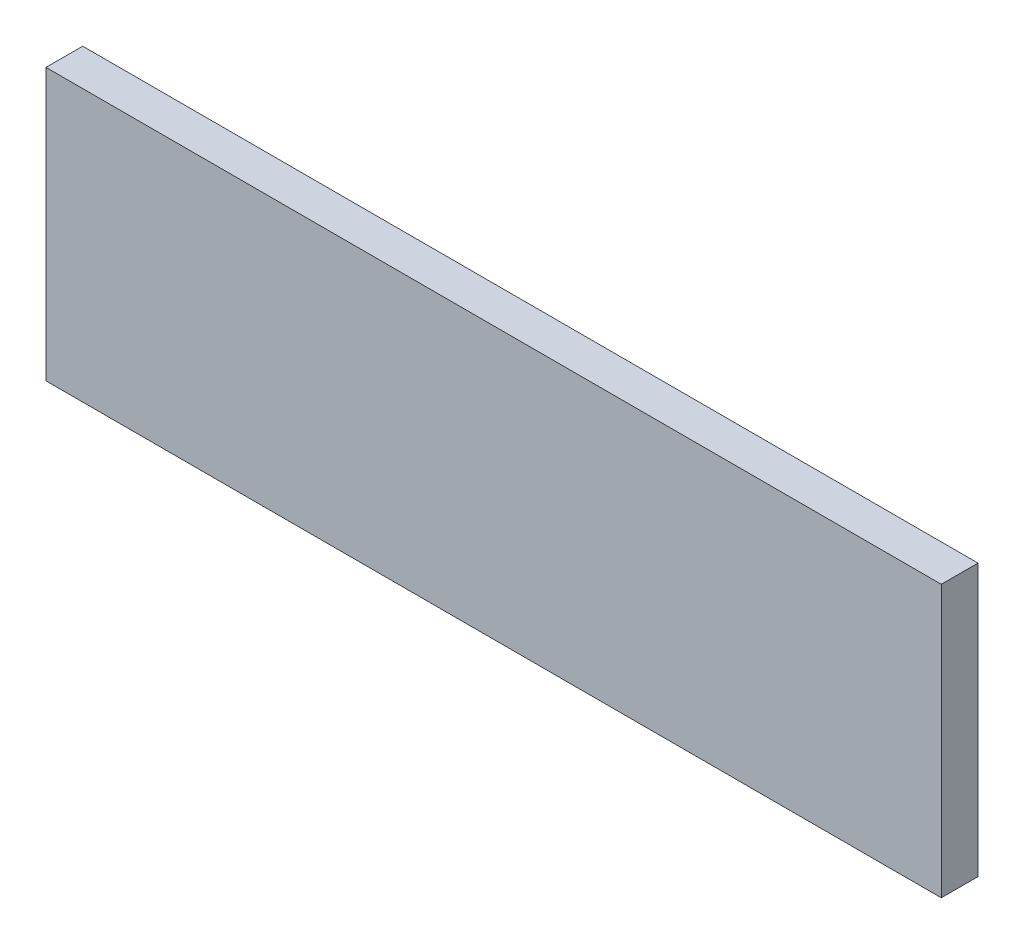
SolidWorks part; units mm, degrees
ref_plane "Front Plane" through (0, 0, 0) normal (0, 0, 1) x (1, 0, 0)
ref_plane "Top Plane" through (0, 0, 0) normal (0, 1, 0) x (1, 0, 0)
ref_plane "Right Plane" through (0, 0, 0) normal (1, 0, 0) x (0, 0, -1)
sketch "Sketch1" plane through (0, 0, 0) normal (0, 0, 1) x (1, 0, 0)
  line L0 (-67, -7) -> (-67, 67) construction
  line L1 (-67, 67) -> (177, 67)
  line L2 (-67, 67) -> (-67, -7)
  line L3 (-67, -7) -> (177, -7)
  line L4 (177, 67) -> (177, -7)
  line L5 (-67, 67) -> (177, 67) construction
  line L6 (177, 67) -> (177, -7) construction
  line L7 (177, -7) -> (-67, -7) construction
extrude "Boss-Extrude1" add sketch "Sketch1" along normal blind 10
